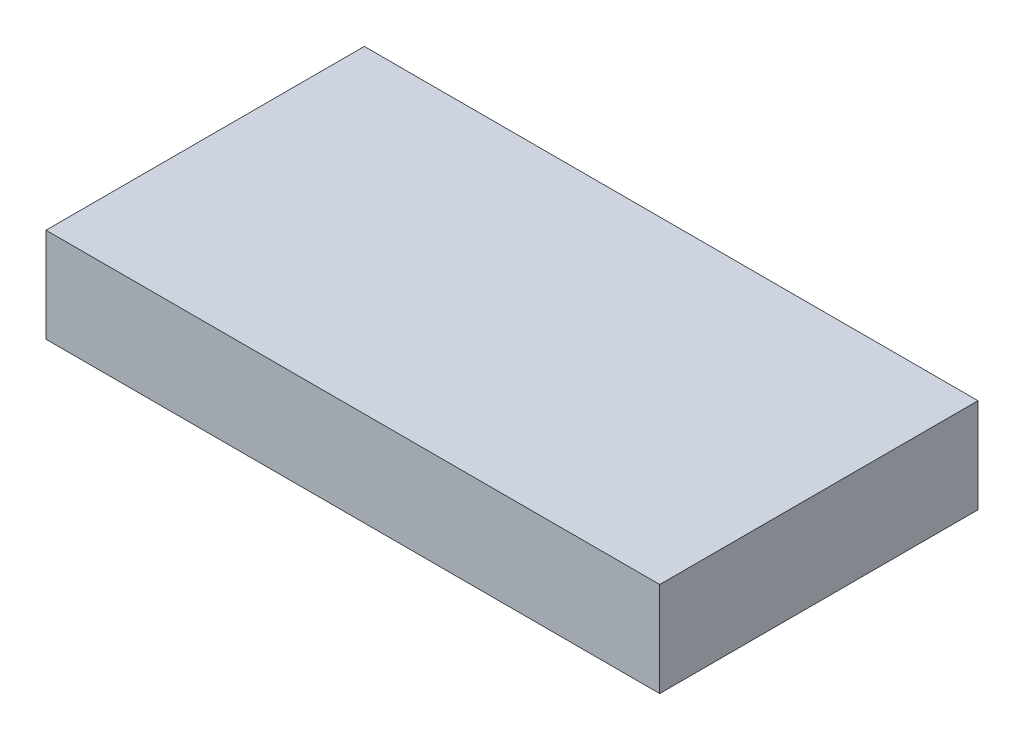
SolidWorks part; units mm, degrees
ref_plane "Front Plane" through (0, 0, 0) normal (0, 0, 1) x (1, 0, 0)
ref_plane "Top Plane" through (0, 0, 0) normal (0, 1, 0) x (1, 0, 0)
ref_plane "Right Plane" through (0, 0, 0) normal (1, 0, 0) x (0, 0, -1)
sketch "Sketch1" plane through (0, 0, 0) normal (0, 1, 0) x (1, 0, 0)
  line L1 (0, 0) -> (64.9517, 0)
  line L2 (0, 0) -> (0, 33.689)
  line L3 (0, 33.689) -> (64.9517, 33.689)
  line L4 (64.9517, 0) -> (64.9517, 33.689)
extrude "Boss-Extrude1" add sketch "Sketch1" along normal blind 10
